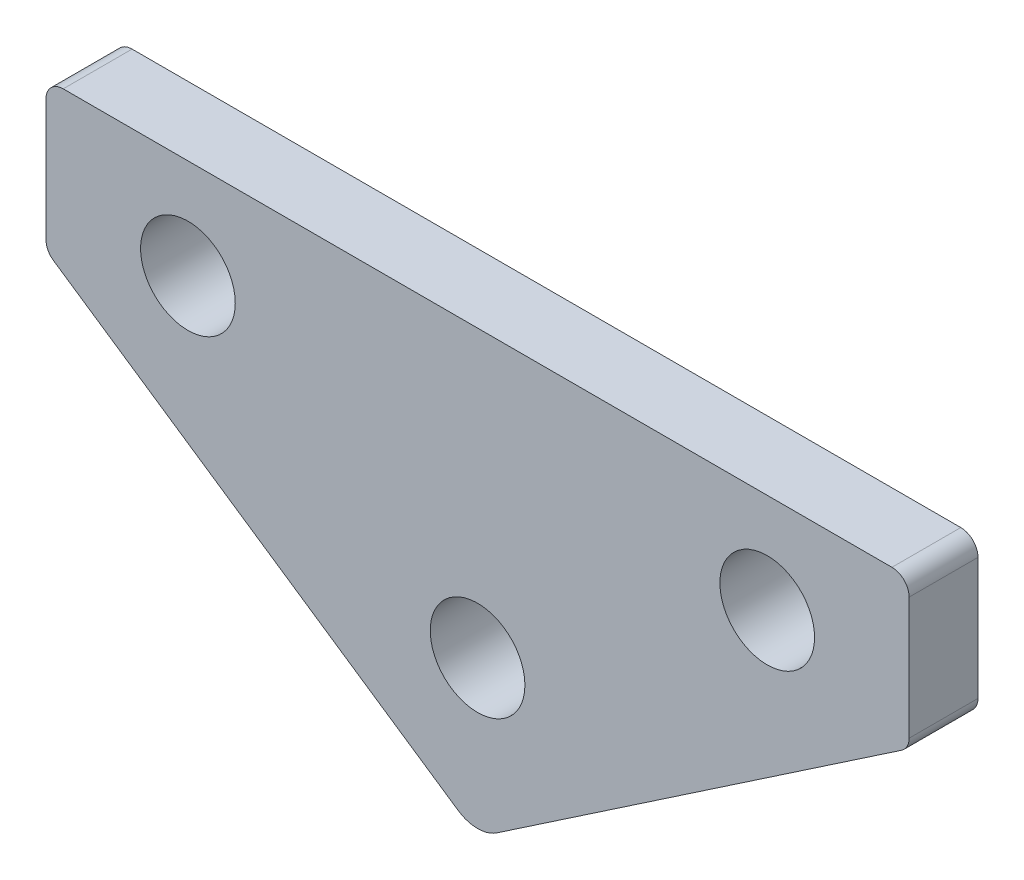
SolidWorks part; units mm, degrees
ref_plane "Front Plane" through (0, 0, 0) normal (0, 0, 1) x (1, 0, 0)
ref_plane "Top Plane" through (0, 0, 0) normal (0, 1, 0) x (1, 0, 0)
ref_plane "Right Plane" through (0, 0, 0) normal (1, 0, 0) x (0, 0, -1)
sketch "Sketch1" plane through (0, 0, 0) normal (0, 0, 1) x (1, 0, 0)
  line L0 (0, 0) -> (-16.8271, 10.8097)
  line L1 (0, 0) -> (0, 16.5927) construction
  line L2 (24.0722, 16.5927) -> (-24.0722, 16.5927)
  line L3 (-25.0722, 15.5927) -> (-25.0722, 8.4955)
  line L4 (-24.6327, 7.6673) -> (-1.121, -8.2449)
  line L5 (24.6327, 7.6673) -> (1.121, -8.2449)
  line L6 (25.0722, 15.5927) -> (25.0722, 8.4955)
  circle A0 centre (0, 0) radius 2.75
  circle A1 centre (-16.8271, 10.8097) radius 2.75
  circle A2 centre (16.8271, 10.8097) radius 2.75
  arc A3 (24.0722, 16.5927) -> (25.0722, 15.5927) centre (24.0722, 15.5927) cw
  arc A4 (24.6327, 7.6673) -> (25.0722, 8.4955) centre (24.0722, 8.4955) ccw
  arc A5 (-25.0722, 8.4955) -> (-24.6327, 7.6673) centre (-24.0722, 8.4955) ccw
  arc A6 (-25.0722, 15.5927) -> (-24.0722, 16.5927) centre (-24.0722, 15.5927) cw
  arc A7 (-1.121, -8.2449) -> (1.121, -8.2449) centre (0, -6.5886) ccw
  point P15 (25.0722, 16.5927)
  point P18 (25.0722, 7.9647)
  point P21 (-25.0722, 7.9647)
  point P24 (-25.0722, 16.5927)
  point P27 (0, -9.0036)
  dimension "D1" = 5.5
  dimension "D3" = 1
  dimension "D4" = 2
  dimension "D2" = 20
extrude "Boss-Extrude1" add sketch "Sketch1" along normal blind 4
